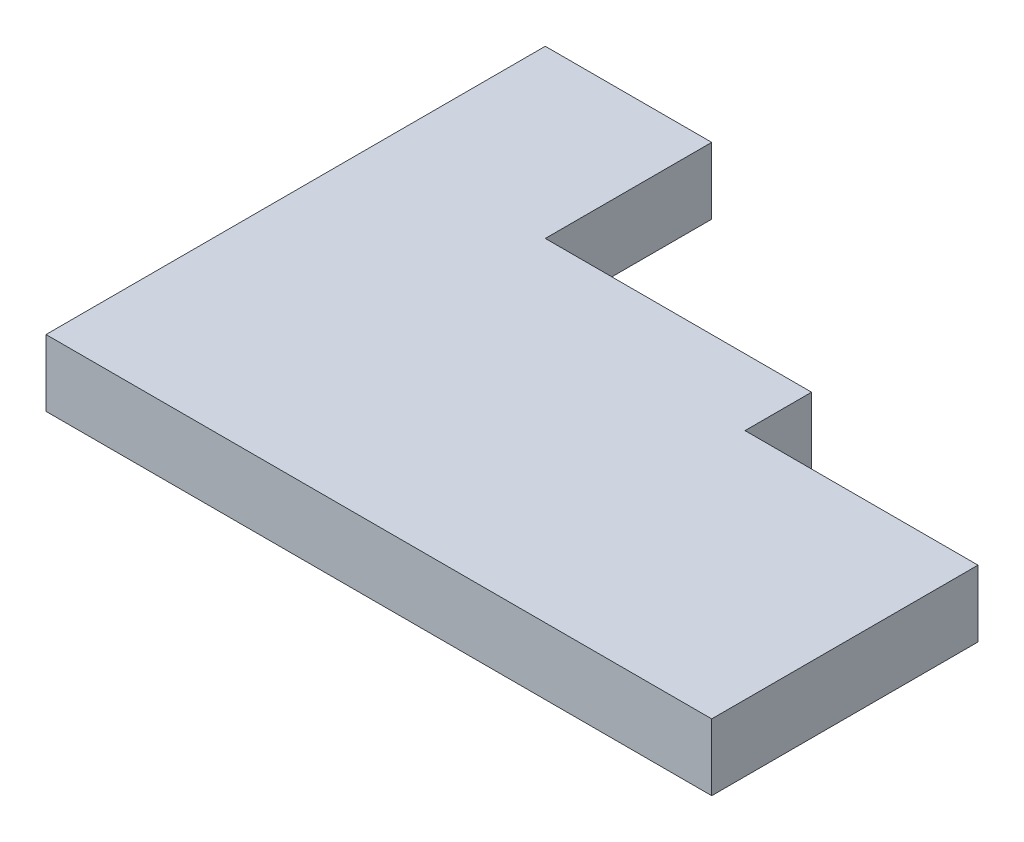
SolidWorks part; units mm, degrees
ref_plane "Front Plane" through (0, 0, 0) normal (0, 0, 1) x (1, 0, 0)
ref_plane "Top Plane" through (0, 0, 0) normal (0, 1, 0) x (1, 0, 0)
ref_plane "Right Plane" through (0, 0, 0) normal (1, 0, 0) x (0, 0, -1)
sketch "Sketch1" plane through (0, 0, 0) normal (0, 1, 0) x (1, 0, 0)
  line L1 (0, 0) -> (20, 0)
  line L2 (0, 0) -> (0, 15)
  line L3 (0, 15) -> (5, 15)
  line L4 (20, 0) -> (20, 8)
  line L6 (5, 15) -> (5, 10)
  line L7 (5, 10) -> (13, 10)
  line L10 (13, 10) -> (13, 8)
  line L11 (13, 8) -> (20, 8)
  dimension "D1" = 20
  dimension "D3" = 10
  dimension "D4" = 15
  dimension "D5" = 5
  dimension "D6" = 8
extrude "Boss-Extrude1" add sketch "Sketch1" along normal blind 2 contours L2 L3 L6 L7 L10 L11 L4 L1
equation "\"A\"= 8"
equation "\"D2@Sketch1\"=\"A\""
